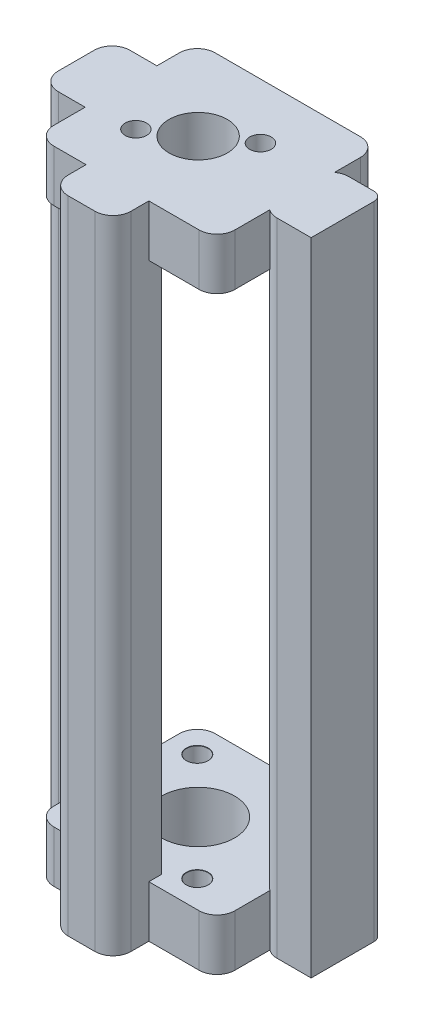
SolidWorks part; units mm, degrees
ref_plane "Front Plane" through (0, 0, 0) normal (0, 0, 1) x (1, 0, 0)
ref_plane "Top Plane" through (0, 0, 0) normal (0, 1, 0) x (1, 0, 0)
ref_plane "Right Plane" through (0, 0, 0) normal (1, 0, 0) x (0, 0, -1)
sketch "Sketch1" plane through (0, 0, 0) normal (0, 1, 0) x (1, 0, 0)
  line L0 (0, 9) -> (0, -9) construction
  line L1 (-9.1, -9) -> (11.1, -9)
  line L2 (-9.1, -9) -> (-9.1, 9)
  line L3 (-9.1, 9) -> (11.1, 9)
  line L4 (11.1, -9) -> (11.1, 9)
  line L5 (-9.1, 0) -> (11.1, 0) construction
  point P0 (0, 0)
  dimension "D1" = 9.1
  dimension "D2" = 18
  dimension "D3" = 11.1
extrude "Boss-Extrude1" add sketch "Sketch1" along normal blind 5.75
sketch "Sketch2" plane through (0, 5.75, 0) normal (0, 1, 0) x (1, 0, 0)
  line L0 (1, 9) -> (1, -9) construction
  line L1 (11.1, 9) -> (-9.1, 9) construction
  line L2 (-9.1, -9) -> (11.1, -9) construction
  line L3 (-9.1, 0) -> (11.1, 0) construction
  line L4 (-9.1, 9) -> (-9.1, -9) construction
  line L5 (11.1, -9) -> (11.1, 9) construction
  line L6 (-9.1, 9) -> (8.9, -9) construction
  line L7 (-9.1, -9) -> (8.9, 9) construction
  line L8 (8.9, 9) -> (8.9, -9) construction
  dimension "D1" = 18
  dimension "D2" = 18
hole_wizard "M2 Clearance Hole1" positions "Sketch3" profile "Sketch4" hole size "M2" standard "ANSI Metric" end condition up to next
sketch "Sketch3" plane through (0, 5.75, 0) normal (0, 1, 0) x (1, 0, 0)
  line L0 (-9.1, 9) -> (8.9, -9) construction
  line L1 (-9.1, -9) -> (8.9, 9) construction
  point P0 (-6.1, 6)
  point P4 (5.9, 6)
  point P8 (-6.1, -6)
  point P10 (5.9, -6)
  dimension "D1" = 12
  dimension "D2" = 12
sketch "Sketch4" plane through (-6.1, 5.75, -6) normal (1, 0, 0) x (0, 0, 1)
  line L0 (0, 0) -> (0, 5.75)
  line L1 (0, 5.75) -> (1.2, 5.75)
  line L2 (1.2, 5.75) -> (1.2, 0.025)
  line L3 (1.2, 0.025) -> (1.225, 0)
  line L5 (1.225, 0) -> (0, 0)
  line L6 (-1.2, 0.025) -> (-1.225, 0) construction
  line L11 (0, -6.35) -> (0, 107.95) construction
  dimension "Thru Hole Dia." = 2.4
  dimension "Thru Hole Depth" = 5.75
  dimension "Near C'Sink Dia." = 2.45
  dimension "Near C'Sink Angle" = 90
sketch "Sketch5" plane through (0, 5.75, 0) normal (0, 1, 0) x (1, 0, 0)
  line L0 (0, -13) -> (0, -7.6) construction
  line L1 (-14.1, -3.5) -> (-8.3, -3.5)
  line L2 (-14.1, -3.5) -> (-14.1, 4.5)
  line L3 (-14.1, 4.5) -> (-8.3, 4.5)
  line L4 (-8.3, -3.5) -> (-8.3, 4.5)
  line L5 (11.1, 0) -> (-9, 0) construction
  line L6 (11.1, -9) -> (11.1, 9) construction
  line L15 (3.5, -7.6) -> (-1.5, -7.6)
  line L16 (-3.5, -9) -> (-3.5, -7.6)
  line L17 (3.5, -9) -> (0, -9) construction
  line L18 (3.5, -9) -> (3.5, -7.6)
  line L19 (0, 9) -> (0, -9) construction
  line L20 (11.1, 9) -> (-9.1, 9) construction
  line L24 (-9.1, -9) -> (11.1, -9) construction
  line L25 (0, -7.6) -> (-1.5, -7.6) construction
  line L26 (-1.5, -7.6) -> (-3.5, -7.6)
  line L27 (-1.5, -7.6) -> (0, -7.6) construction
  line L29 (10.3, 4.5) -> (16.1, 4.5)
  line L30 (10.3, 4.5) -> (10.3, -3.5)
  line L31 (-9.1, 3.5) -> (-9.1, -3.5) construction
  line L32 (-9.1, 9) -> (-9.1, -9) construction
  line L33 (11.1, 3.5) -> (11.1, -3.5) construction
  line L34 (-3.5, -9) -> (-3.5, -13)
  line L35 (-3.5, -13) -> (3.5, -13)
  line L36 (3.5, -13) -> (3.5, -9)
  line L37 (0, -9) -> (-3.5, -9) construction
  line L38 (10.3, -3.5) -> (16.1, -3.5)
  line L39 (16.1, 4.5) -> (16.1, -3.5)
  point P27 (0, 0)
  dimension "D5" = 1.4
  dimension "D6" = 7
  dimension "D1" = 0.8
  dimension "D10" = 5
  dimension "D12" = 4
  dimension "D2" = 3.5
  dimension "D13" = 4.5
  dimension "D4" = 0.8
  dimension "D7" = 4.5
  dimension "D11" = 3.5
  dimension "D3" = 5
extrude "Boss-Extrude2" add sketch "Sketch5" along normal blind 60
sketch "Sketch6" plane through (0, 5.75, 0) normal (0, 1, 0) x (1, 0, 0)
  circle A0 centre (0, 0) radius 4.0625
  dimension "D1" = 8.125
extrude "Cut-Extrude1" cut sketch "Sketch6" against normal up to surface (5.75 mm away) up to face at (-6.1, 0, -7.2)
ref_plane "Plane1" through (0, 35.75, 0) normal (0, 1, 0) x (1, 0, 0)
mirror "Mirror1" about plane through (0, 35.75, 0) normal (0, 1, 0) of "Boss-Extrude1"
sketch "Sketch7" plane through (0, 71.5, 0) normal (0, 1, 0) x (1, 0, 0)
  line L0 (-5, 9) -> (-5, -9) construction
  line L1 (11.1, 9) -> (-9.1, 9) construction
  line L2 (-9.1, -9) -> (11.1, -9) construction
  line L3 (5, 9) -> (5, -9) construction
  line L4 (-9.1, 0) -> (11.1, 0) construction
  line L5 (-9.1, 9) -> (-9.1, -9) construction
  line L6 (11.1, -9) -> (11.1, 9) construction
  line L7 (-9.1, 9) -> (11.1, -9) construction
  line L8 (-9.1, -9) -> (11.1, 9) construction
  circle A0 centre (0, 0) radius 3.25
  circle A1 centre (-5, 0) radius 1 construction
  circle A2 centre (5, 0) radius 1 construction
  dimension "D3" = 6.5
  dimension "D4" = 2
  dimension "D1" = 5
  dimension "D2" = 5
extrude "Cut-Extrude2" cut sketch "Sketch7" against normal up to surface (5.75 mm away) up to face at (0.75, 65.75, 1.825)
fillet "Fillet1" radius 2 8 edges at (11.1, 2.875, -9) (-9.1, 2.875, -9) (-9.1, 2.875, 9) (11.1, 2.875, 9) (11.1, 68.625, -9) (-9.1, 68.625, -9) (11.1, 68.625, 9) (-9.1, 68.625, 9)
hole_wizard "M2 Clearance Hole2" positions "Sketch8" profile "Sketch10" hole size "M2" standard "ANSI Metric"
sketch "Sketch8" plane through (0, 71.5, 0) normal (0, 1, 0) x (1, 0, 0)
  line L1 (-9.1, -9) -> (11.1, 9) construction
  line L2 (-4.1424, -2.8001) -> (4.1424, 2.8001)
  point P7 (-4.1424, -2.8001)
  point P11 (4.1424, 2.8001)
  dimension "D1" = 5
  dimension "D2" = 5
sketch "Sketch10" plane through (-4.1424, 71.5, 2.8001) normal (1, 0, 0) x (0, 0, 1)
  line L0 (0, 0) -> (0, 6.471)
  line L1 (0, 6.471) -> (1.2, 5.75)
  line L2 (1.2, 5.75) -> (1.2, 0)
  line L5 (1.2, 0) -> (0, 0)
  line L10 (0, 6.471) -> (-1.2, 5.75) construction
  line L11 (0, -6.35) -> (0, 107.95) construction
  dimension "Hole Dia." = 2.4
  dimension "Hole Depth" = 5.75
  dimension "Drill Angle" = 118
sketch "Sketch11" plane through (0, 65.75, 0) normal (0, 1, 0) x (1, 0, 0)
  line L0 (-7.1, -9) -> (9.1, -9) construction
  line L1 (-14.1, -3.5) -> (-9.1, -3.5)
  line L2 (-14.1, -3.5) -> (-14.1, 4.5)
  line L3 (-14.1, 4.5) -> (-9.1, 4.5)
  line L4 (-9.1, -3.5) -> (-9.1, 4.5)
  line L5 (16.1, -3.5) -> (11.1, -3.5)
  line L6 (16.1, -3.5) -> (16.1, 4.5)
  line L7 (16.1, 4.5) -> (11.1, 4.5)
  line L8 (11.1, -3.5) -> (11.1, 4.5)
  line L9 (3.5, -13) -> (-3.5, -13)
  line L10 (3.5, -13) -> (3.5, -9)
  line L11 (3.5, -9) -> (-3.5, -9)
  line L12 (-3.5, -13) -> (-3.5, -9)
  line L13 (-3.5, -9) -> (3.5, -9) construction
extrude "Boss-Extrude3" add sketch "Sketch11" along normal up to surface (5.75 mm away) up to face at (-4.1424, 71.5, 4.0001)
sketch "Sketch12" plane through (0, 5.75, 0) normal (0, -1, 0) x (1, 0, 0)
  line L0 (-9.1, -7) -> (-9.1, 7) construction
  line L1 (-14.1, -4.5) -> (-9.1, -4.5)
  line L2 (-14.1, -4.5) -> (-14.1, 3.5)
  line L3 (-14.1, 3.5) -> (-9.1, 3.5)
  line L4 (-9.1, -4.5) -> (-9.1, 3.5)
  line L5 (-9.1, -4.5) -> (-9.1, 3.5) construction
  line L6 (-14.1, 3.5) -> (-9.1, 3.5) construction
  line L7 (-3.5, 13) -> (3.5, 13)
  line L8 (-3.5, 13) -> (-3.5, 9)
  line L9 (-3.5, 9) -> (3.5, 9)
  line L10 (3.5, 13) -> (3.5, 9)
  line L11 (16.1, -4.5) -> (11.1, -4.5)
  line L12 (16.1, -4.5) -> (16.1, 3.5)
  line L13 (16.1, 3.5) -> (11.1, 3.5)
  line L14 (11.1, -4.5) -> (11.1, 3.5)
  line L15 (16.1, 3.5) -> (16.1, -4.5) construction
  line L16 (16.1, -4.5) -> (11.1, -4.5) construction
extrude "Boss-Extrude4" add sketch "Sketch12" along normal up to surface (5.75 mm away) up to face at (0, 0, -4.0625)
fillet "Fillet2" radius 2 6 edges at (-14.1, 35.75, -4.5) (-14.1, 35.75, 3.5) (3.5, 35.75, 13) (-3.5, 35.75, 13) (10.3, 35.75, 3.5) (10.3, 35.75, -4.5)
sketch "Sketch13" plane through (-8.3, 0, 0) normal (1, 0, 0) x (0, 0, -1)
  line L0 (4.5, 65.75) -> (4.5, 5.75) construction
  line L1 (4.5, 5.75) -> (-3.5, 5.75)
  line L2 (4.5, 5.75) -> (4.5, 48.75)
  line L3 (4.5, 48.75) -> (-3.5, 48.75)
  line L4 (-3.5, 5.75) -> (-3.5, 48.75)
  line L5 (-3.5, 65.75) -> (-3.5, 5.75) construction
  line L7 (-3.5, 65.75) -> (4.5, 65.75) construction
  line L8 (4.1, 5.75) -> (7, 5.75) construction
  dimension "D2" = 17
ref_plane "Plane2" through (3.9, 0, 0) normal (1, 0, 0) x (0, 0, -1)
ref_plane "Plane3" through (0, 5.75, 0) normal (0, 1, 0) x (1, 0, 0)
sketch "Sketch14" plane through (0, 0, -4.5) normal (0, 0, -1) x (-1, 0, 0)
  line L0 (-12.3, 71.5) -> (-12.3, 0) construction
  line L1 (-12.3, 10) -> (12.1, 10)
  line L2 (-12.3, 10) -> (-12.3, 11)
  line L3 (-12.3, 11) -> (12.1, 11)
  line L4 (12.1, 10) -> (12.1, 11)
  line L5 (12.1, 0) -> (12.1, 71.5) construction
  line L6 (-16.1, 0) -> (-12.3, 0) construction
  dimension "D1" = 10
  dimension "D2" = 1
extrude "Cut-Extrude3" cut sketch "Sketch14" against normal blind 2
fillet "Fillet3" radius 1 4 edges at (-10.2, 11, -4.5) (-10.2, 10, -4.5) (10.8858, 10, -3.9142) (10.8858, 11, -3.9142)
fillet "Fillet4" radius 1 7 edges at (-8.3, 11, -3) (-8.3, 11.2929, -4.2071) (-8.3, 10, -3) (-8.3, 9.7071, -4.2071) (16.1, 35.75, -4.5) (-8.3, 38.875, -4.5) (-8.3, 7.375, -4.5)
equation "\"D5@Sketch5\"=2-0.6"
